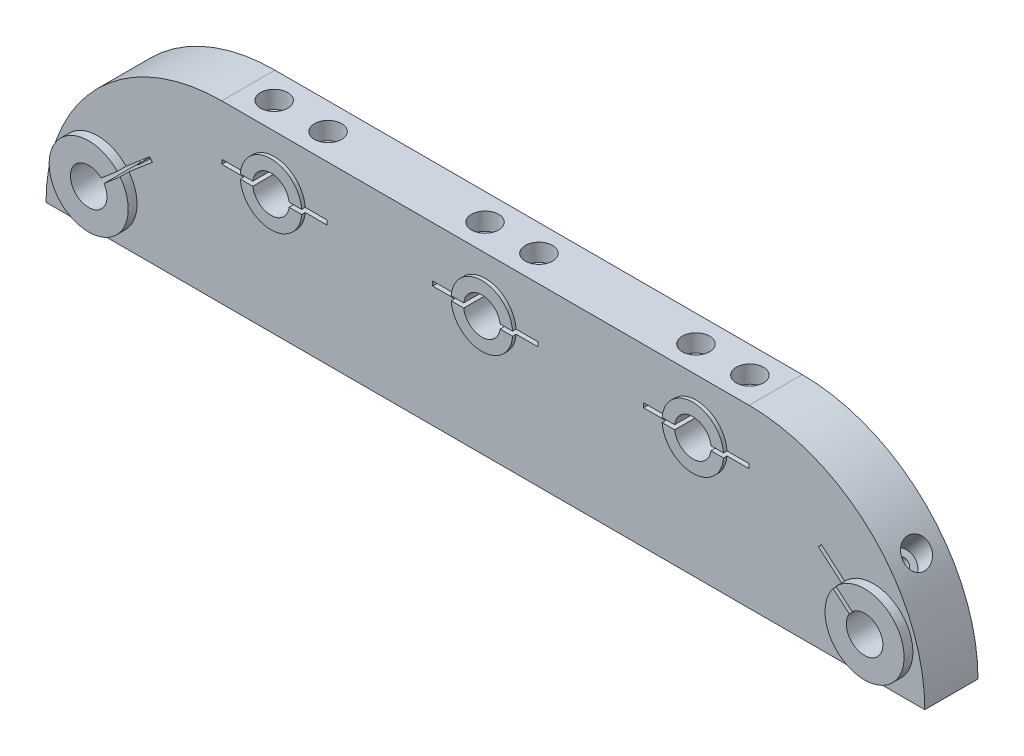
SolidWorks part; units mm, degrees
ref_plane "Front Plane" through (0, 0, 0) normal (0, 0, 1) x (1, 0, 0)
ref_plane "Top Plane" through (0, 0, 0) normal (0, 1, 0) x (1, 0, 0)
ref_plane "Right Plane" through (0, 0, 0) normal (1, 0, 0) x (0, 0, -1)
sketch "Sketch1" plane through (0, 0, 0) normal (0, 0, 1) x (1, 0, 0)
  line L0 (-48, 8) -> (0, 8) construction
  line L1 (-60, 20) -> (60, 20)
  line L3 (-100, -20) -> (100, -20)
  line L5 (-100, 20) -> (100, -20) construction
  line L6 (-100, -20) -> (100, 20) construction
  line L7 (0, 8) -> (48, 8) construction
  line L8 (0, 37.7846) -> (0, -45.3301) construction
  line L9 (-110.8398, 0) -> (122.7505, 0) construction
  circle A0 centre (0, 8) radius 4.165
  circle A1 centre (48, 8) radius 4.165
  circle A2 centre (-48, 8) radius 4.165
  circle A3 centre (-88.2843, -10) radius 4.165
  circle A4 centre (88.2843, -10) radius 4.165
  circle A5 centre (-48, 8) radius 19 construction
  arc A7 (-60, 20) -> (-100, -20) centre (-60, -20) ccw
  arc A8 (60, 20) -> (100, -20) centre (60, -20) cw
  circle A9 centre (-88.2843, -10) radius 10 construction
  circle A10 centre (88.2843, -10) radius 10 construction
  point P0 (0, 0)
  point P25 (0, 20)
  point P26 (0, -20)
  dimension "D4" = 8.33
  dimension "D6" = 38
  dimension "D1" = 40
  dimension "D2" = 200
  dimension "D3" = 12
  dimension "D5" = 48
  dimension "D7" = 40
  dimension "D8" = 200
extrude "Boss-Extrude1" add sketch "Sketch1" along normal blind 12.1
sketch "Sketch2" plane through (0, 0, 12.1) normal (0, 0, 1) x (1, 0, 0)
  circle A1 centre (48, 8) radius 4.165 construction
  circle A2 centre (0, 8) radius 4.165 construction
  circle A3 centre (-48, 8) radius 4.165 construction
  circle A6 centre (48, 8) radius 4.165
  circle A7 centre (0, 8) radius 4.165
  circle A8 centre (-48, 8) radius 4.165
  circle A11 centre (-48, 8) radius 7
  circle A12 centre (0, 8) radius 7
  circle A13 centre (48, 8) radius 7
  dimension "D1" = 14
extrude "Boss-Extrude3" add sketch "Sketch2" along normal blind 0.8
sketch "Sketch4" plane through (0, 0, 12.1) normal (0, 0, 1) x (1, 0, 0)
  circle A0 centre (88.2843, -10) radius 4.165 construction
  circle A1 centre (-88.2843, -10) radius 4.165 construction
  circle A2 centre (88.2843, -10) radius 4.165
  circle A3 centre (-88.2843, -10) radius 4.165
  circle A4 centre (-88.2843, -10) radius 9
  circle A5 centre (88.2843, -10) radius 9
  dimension "D1" = 18
extrude "Boss-Extrude4" add sketch "Sketch4" along normal blind 2
sketch "Sketch6" plane through (0, 0, 0) normal (0, 0, -1) x (-1, 0, 0)
  line L0 (-48, 8) -> (48, 8) construction
  line L1 (-100, -20) -> (-67.196, 8) construction
  line L2 (100, -20) -> (67.196, 8) construction
  line L3 (0, 24.4792) -> (0, -10) construction
  line L11 (20, 8.3) -> (20, 7.7)
  line L16 (88.6089, -9.6197) -> (76.4392, 0.7678)
  line L17 (88.6089, -9.6197) -> (87.9597, -10.3803)
  line L18 (87.9597, -10.3803) -> (75.79, 0.0072)
  line L19 (76.4392, 0.7678) -> (75.79, 0.0072)
  line L20 (-87.9597, -10.3803) -> (-75.79, 0.0072)
  line L21 (-76.4392, 0.7678) -> (-75.79, 0.0072)
  line L22 (-88.6089, -9.6197) -> (-76.4392, 0.7678)
  line L23 (-88.6089, -9.6197) -> (-87.9597, -10.3803)
  line L37 (-60, 8.5) -> (-36, 8.5)
  line L38 (-60, 8.5) -> (-60, 7.5)
  line L39 (-60, 7.5) -> (-36, 7.5)
  line L40 (-36, 8.5) -> (-36, 7.5)
  line L41 (-60, 8.5) -> (-36, 7.5) construction
  line L42 (-60, 7.5) -> (-36, 8.5) construction
  line L43 (-12, 8.5) -> (12, 8.5)
  line L44 (-12, 8.5) -> (-12, 7.5)
  line L45 (-12, 7.5) -> (12, 7.5)
  line L46 (12, 8.5) -> (12, 7.5)
  line L47 (-12, 8.5) -> (12, 7.5) construction
  line L48 (-12, 7.5) -> (12, 8.5) construction
  line L49 (36, 8.5) -> (60, 8.5)
  line L50 (36, 8.5) -> (36, 7.5)
  line L51 (36, 7.5) -> (60, 7.5)
  line L52 (60, 8.5) -> (60, 7.5)
  line L53 (36, 8.5) -> (60, 7.5) construction
  line L54 (36, 7.5) -> (60, 8.5) construction
  circle A1 centre (-88.2843, -10) radius 4.165 construction
  circle A2 centre (-88.2843, -10) radius 4.165 construction
  circle A3 centre (88.2843, -10) radius 4.165 construction
  circle A4 centre (88.2843, -10) radius 4.165 construction
  point P6 (-48, 8)
  point P24 (0, 8)
  point P29 (48, 8)
  point P32 (88.2843, -10)
  point P48 (0, 8)
  circle M18 centre (-48, 8) radius 4.165
  dimension "D1" = 24
  dimension "D2" = 1
  dimension "D3" = 1
  dimension "D4" = 16
extrude "Cut-Extrude2" cut sketch "Sketch6" against normal through all both and the other way through all contours L38 L39 L37 M18 | L43 L46 L45 L44 | L49 L52 L51 L50 | L20 L21 L22 L23 | L16 L19 L18 L17
sketch "Sketch8" plane through (0, 7.5, 0) normal (0, 1, 0) x (1, 0, 0)
  line L0 (52.1349, 0) -> (52.1349, -12.9) construction
  line L1 (60, -12.1) -> (60, 0) construction
  line L2 (60, -12.1) -> (60, 0) construction
  line L3 (62.9889, -6.05) -> (-85.4727, -6.05) construction
  line L4 (43.8651, -12.9) -> (43.8651, 0) construction
  line L6 (4.1349, 0) -> (4.1349, -12.9) construction
  line L7 (0, -7.755) -> (0, 7.755) construction
  circle A0 centre (54.1349, -6.05) radius 1.6
  circle A1 centre (41.8651, -6.05) radius 1.6
  circle A2 centre (6.1349, -6.05) radius 1.6
  circle A3 centre (-41.8651, -6.05) radius 1.6
  circle A4 centre (-6.1349, -6.05) radius 1.6
  circle A5 centre (-54.1349, -6.05) radius 1.6
  point P13 (60, -6.05)
  dimension "D1" = 3.2
  dimension "D2" = 2
  dimension "D4" = 2
  dimension "D3" = 2
extrude "Cut-Extrude3" cut sketch "Sketch8" against normal through all both and the other way through all
sketch "Sketch9" plane through (31.9476, 37.429, 0) normal (0.6492, 0.7606, 0) x (0.7606, -0.6492, 0)
  line L0 (69.5067, -14.1) -> (69.5067, 0) construction
  line L1 (57.6415, -12.1) -> (57.6415, 0) construction
  line L2 (57.6415, -12.1) -> (57.6415, 0) construction
  circle A0 centre (67.5067, -6.05) radius 1.6
  point P6 (57.6415, -6.05)
  dimension "D1" = 3.2
  dimension "D2" = 2
extrude "Cut-Extrude4" cut sketch "Sketch9" against normal up to next and the other way up to next
sketch "Sketch10" plane through (-31.9476, 37.429, 0) normal (-0.6492, 0.7606, 0) x (0.7606, 0.6492, 0)
  line L0 (-57.6415, -12.1) -> (-57.6415, 0) construction
  line L1 (-57.6415, -12.1) -> (-57.6415, 0) construction
  line L2 (-69.5067, -14.1) -> (-69.5067, 0) construction
  circle A0 centre (-67.5067, -6.05) radius 1.6
  point P6 (-57.6415, -6.05)
  dimension "D1" = 3.2
  dimension "D2" = 2
extrude "Cut-Extrude5" cut sketch "Sketch10" against normal up to next and the other way up to next
sketch "Sketch11" plane through (0, 20, 0) normal (0, 1, 0) x (1, 0, 0)
  circle A0 centre (-54.1349, -6.05) radius 3.1
  circle A1 centre (-41.8651, -6.05) radius 3.1
  circle A2 centre (-6.1349, -6.05) radius 3.1
  circle A3 centre (6.1349, -6.05) radius 3.1
  circle A4 centre (41.8651, -6.05) radius 3.1
  circle A5 centre (54.1349, -6.05) radius 3.1
  dimension "D1" = 6.2
extrude "Cut-Extrude6" cut sketch "Sketch11" against normal blind 4
sketch "Sketch12" plane through (0, -20, 0) normal (0, -1, 0) x (1, 0, 0)
  circle A0 centre (-54.1349, 6.05) radius 3.6
  circle A1 centre (-41.8651, 6.05) radius 3.6
  circle A2 centre (-6.1349, 6.05) radius 3.6
  circle A3 centre (6.1349, 6.05) radius 3.6
  circle A4 centre (41.8651, 6.05) radius 3.6
  circle A5 centre (54.1349, 6.05) radius 3.6
  dimension "D1" = 7.2
extrude "Cut-Extrude7" cut sketch "Sketch12" against normal blind 20
ref_plane "Plane1" through (-37.1414, 43.5138, 0) normal (0.6492, -0.7606, 0) x (-0.7606, -0.6492, 0)
sketch "Sketch13" plane through (-37.1414, 43.5138, 0) normal (0.6492, -0.7606, 0) x (-0.7606, -0.6492, 0)
  circle A0 centre (67.5067, -6.05) radius 3.1
  dimension "D1" = 6.2
extrude "Cut-Extrude8" cut sketch "Sketch13" against normal up to next
ref_plane "Plane2" through (-27.4031, 32.1047, 0) normal (-0.6492, 0.7606, 0) x (0.7606, 0.6492, 0)
sketch "Sketch14" plane through (-27.4031, 32.1047, 0) normal (-0.6492, 0.7606, 0) x (0.7606, 0.6492, 0)
  circle A0 centre (-67.5067, -6.05) radius 3.6
  dimension "D1" = 7.2
extrude "Cut-Extrude9" cut sketch "Sketch14" against normal up to next
ref_plane "Plane3" through (27.4031, 32.1047, 0) normal (0.6492, 0.7606, 0) x (0.7606, -0.6492, 0)
sketch "Sketch15" plane through (27.4031, 32.1047, 0) normal (0.6492, 0.7606, 0) x (0.7606, -0.6492, 0)
  circle A0 centre (67.5067, -6.05) radius 3.6
  dimension "D1" = 7.2
extrude "Cut-Extrude10" cut sketch "Sketch15" against normal up to next
ref_plane "Plane4" through (37.1414, 43.5138, 0) normal (-0.6492, -0.7606, 0) x (-0.7606, 0.6492, 0)
sketch "Sketch16" plane through (37.1414, 43.5138, 0) normal (-0.6492, -0.7606, 0) x (-0.7606, 0.6492, 0)
  circle A0 centre (-67.5067, -6.05) radius 3.1
  dimension "D1" = 6.2
extrude "Cut-Extrude11" cut sketch "Sketch16" against normal up to next
